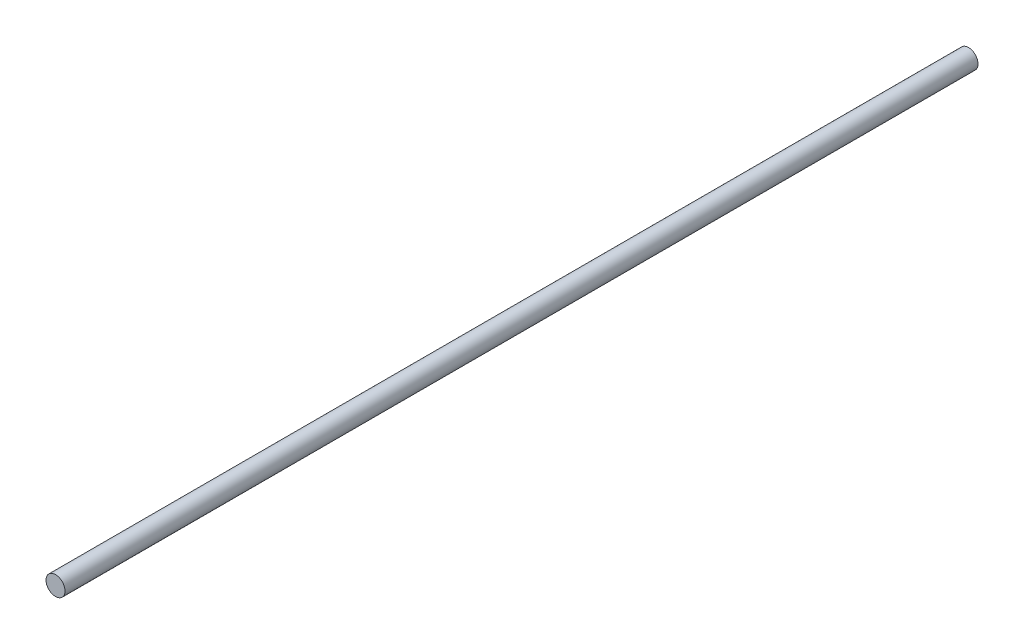
SolidWorks part; units mm, degrees
material "6061-T6 (SS)"
ref_plane "Front" through (0, 0, 0) normal (0, 0, 1) x (1, 0, 0)
ref_plane "Top" through (0, 0, 0) normal (0, 1, 0) x (1, 0, 0)
ref_plane "Right" through (0, 0, 0) normal (1, 0, 0) x (0, 0, -1)
sketch "Sketch1" plane through (0, 0, 0) normal (0, 0, 1) x (1, 0, 0)
  circle A0 centre (0, 0) radius 3.175
  dimension "D1" = 6.35
extrude "Boss-Extrude1" add sketch "Sketch1" along normal blind 304.8
